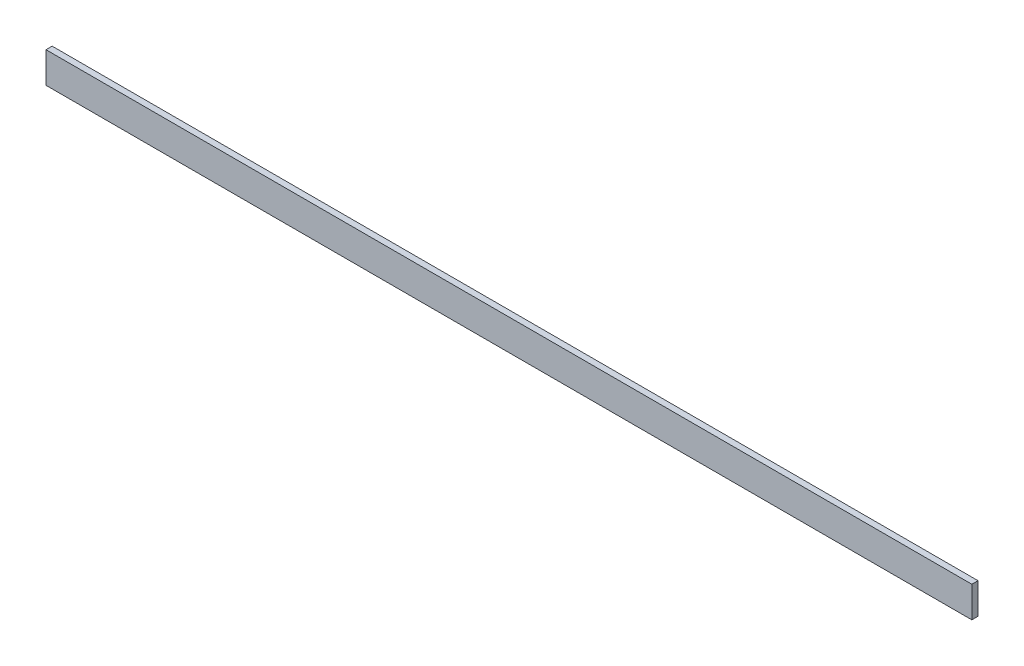
SolidWorks part; units mm, degrees
ref_plane "Front Plane" through (0, 0, 0) normal (0, 0, 1) x (1, 0, 0)
ref_plane "Top Plane" through (0, 0, 0) normal (0, 1, 0) x (1, 0, 0)
ref_plane "Right Plane" through (0, 0, 0) normal (1, 0, 0) x (0, 0, -1)
sketch "Sketch1" plane through (0, 0, 0) normal (0, 0, 1) x (1, 0, 0)
  line L1 (-150, -5) -> (150, -5)
  line L2 (-150, -5) -> (-150, 5)
  line L3 (-150, 5) -> (150, 5)
  line L4 (150, -5) -> (150, 5)
  line L5 (-150, -5) -> (150, 5) construction
  line L6 (-150, 5) -> (150, -5) construction
  point P0 (0, 0)
  dimension "D1" = 10
  dimension "D2" = 300
extrude "Boss-Extrude1" add sketch "Sketch1" along normal blind 2
